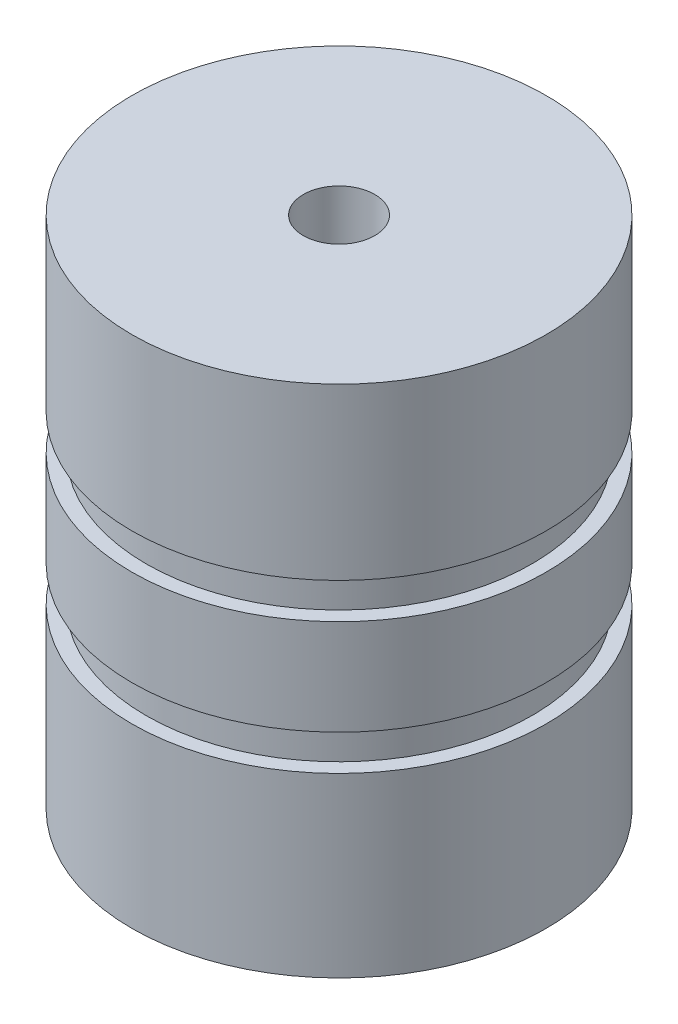
SolidWorks part; units mm, degrees
ref_plane "前视基准面" through (0, 0, 0) normal (0, 0, 1) x (1, 0, 0)
ref_plane "上视基准面" through (0, 0, 0) normal (0, 1, 0) x (1, 0, 0)
ref_plane "右视基准面" through (0, 0, 0) normal (1, 0, 0) x (0, 0, -1)
other "Configuration Table"
sketch "草图1" plane through (0, 0, 0) normal (0, 1, 0) x (1, 0, 0)
  circle A0 centre (0, 0) radius 14.5
  dimension "D1" = 29
extrude "凸台-拉伸1" add sketch "草图1" along normal mid plane 36
sketch "草图2" plane through (0, 0, 0) normal (1, 0, 0) x (0, 0, -1)
  line L0 (0, 24.4564) -> (0, -22.858) construction
  line L1 (14.5, -3.1) -> (13.5, -3.1)
  line L2 (14.5, 6.1) -> (13.5, 6.1)
  line L3 (14.5, -18) -> (14.5, 18) construction
  line L4 (13.5, 6.1) -> (13.5, 3.6)
  line L5 (13.5, 3.6) -> (14.5, 3.6)
  line L6 (14.5, 3.6) -> (14.5, 6.1)
  line L11 (13.5, -3.1) -> (13.5, -5.6)
  line L12 (13.5, -5.6) -> (14.5, -5.6)
  line L13 (14.5, -5.6) -> (14.5, -3.1)
  line L14 (14.5, 18) -> (-14.5, 18) construction
  dimension "D1" = 2.5
  dimension "D2" = 1
  dimension "D3" = 6.7
  dimension "D4" = 11.9
revolve "切除-旋转1" cut sketch "草图2" angle 360 about L0
sketch "草图3" plane through (0, 0, 0) normal (0, 1, 0) x (1, 0, 0)
  circle A0 centre (0, 0) radius 7.5
  dimension "D1" = 15
extrude "切除-拉伸1" cut sketch "草图3" against normal mid plane 11.7
sketch "草图4" plane through (0, 0, 0) normal (0, 1, 0) x (1, 0, 0)
  circle A0 centre (0, 0) radius 2.5
  dimension "D1" = 5
extrude "切除-拉伸2" cut sketch "草图4" along normal up to surface (18 mm away) up to face at (0, 18, 14.5)
sketch "草图5" plane through (0, 0, 0) normal (0, 1, 0) x (1, 0, 0)
  circle A0 centre (0, 0) radius 4
  dimension "D1" = 8
extrude "切除-拉伸3" cut sketch "草图5" against normal up to surface (18 mm away) up to face at (0, -18, 14.5)
